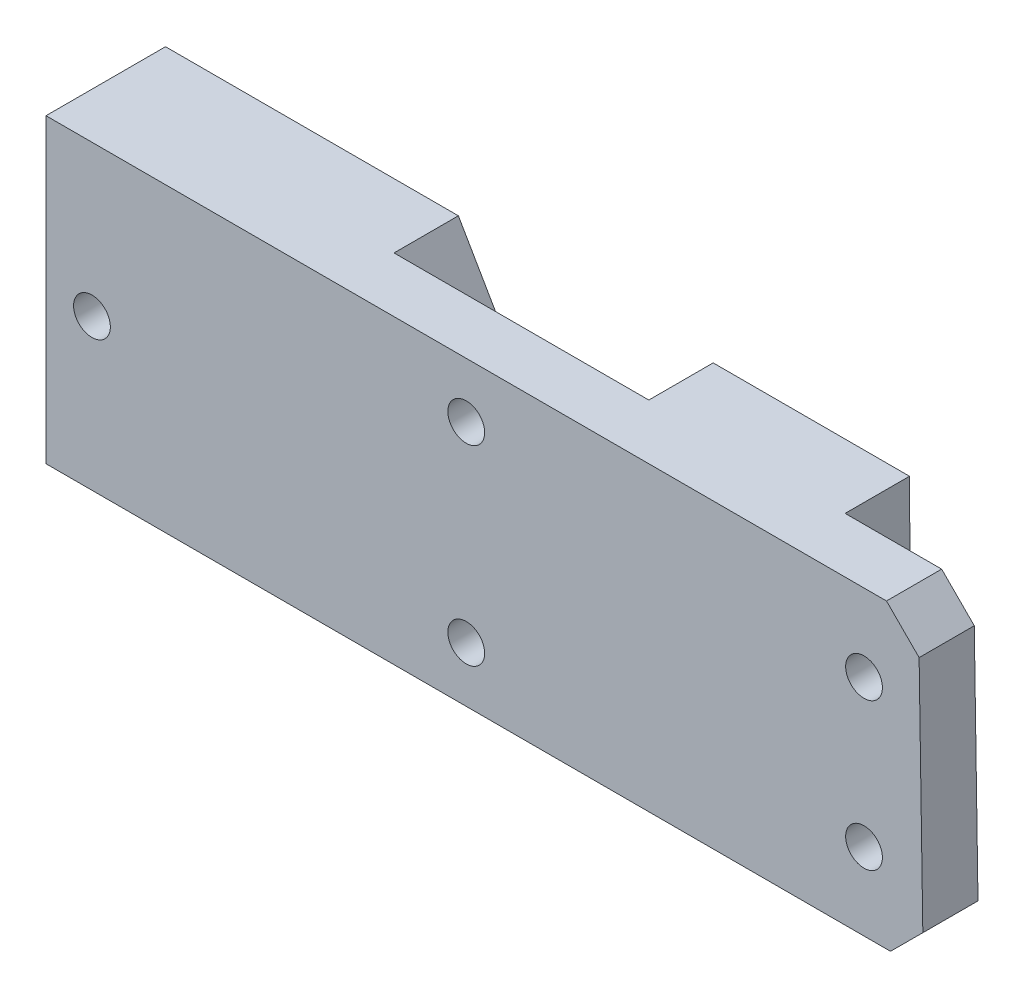
SolidWorks part; units mm, degrees
ref_plane "Front Plane" through (0, 0, 0) normal (0, 0, 1) x (1, 0, 0)
ref_plane "Top Plane" through (0, 0, 0) normal (0, 1, 0) x (1, 0, 0)
ref_plane "Right Plane" through (0, 0, 0) normal (1, 0, 0) x (0, 0, -1)
sketch "Sketch1" plane through (0, 0, 0) normal (0, 0, 1) x (1, 0, 0)
  line L0 (44.15, 19.08) -> (135.5692, 19.08)
  line L1 (12.8834, 142.2085) -> (139.1167, 15.5198) construction
  line L2 (135.5692, 19.08) -> (139.1167, 15.5198)
  line L3 (139.1167, 15.5198) -> (139.5211, -10.196)
  line L4 (139.5211, -10.196) -> (135.9992, -13.7052)
  line L5 (139.5211, -10.196) -> (12.8324, -136.4293) construction
  line L6 (135.9992, -13.7052) -> (44.15, -13.7052)
  line L7 (44.15, 19.08) -> (44.15, -13.7052)
extrude "Boss-Extrude1" add sketch "Sketch1" along normal up to surface (6 mm away)
sketch "Sketch2" plane through (0, 0, 0) normal (0, 0, -1) x (-1, 0, 0)
  line L0 (-125.0695, 19.08) -> (-125.2841, -13.7052)
  line L1 (-125.3536, -24.3126) -> (-125, 29.6874) construction
  line L2 (-135.5692, 19.08) -> (-44.15, 19.08) construction
  line L3 (-44.15, -13.7052) -> (-135.9992, -13.7052) construction
  line L4 (-125.2841, -13.7052) -> (-44.15, -13.7052)
  line L5 (-44.15, -13.7052) -> (-54.15, -3.7052)
  line L6 (-54.15, -3.7052) -> (-54.15, 9.08)
  line L7 (-54.15, 9.08) -> (-44.15, 19.08)
  line L8 (-44.15, 19.08) -> (-125.0695, 19.08)
extrude "Boss-Extrude2" add sketch "Sketch2" along normal up to surface (7 mm away)
sketch "Sketch3" plane through (0, 0, -7) normal (0, 0, -1) x (-1, 0, 0)
  circle A0 centre (-133.1246, 10.6874) radius 2
  circle A1 centre (-133.1246, -5.3126) radius 2
  circle A2 centre (-49.15, 2.6874) radius 2
  dimension "D1" = 4
  dimension "D2" = 4
  dimension "D3" = 4
extrude "Cut-Extrude1" cut sketch "Sketch3" against normal up to next
sketch "Sketch4" plane through (0, 0, 6) normal (0, 0, 1) x (1, 0, 0)
  line L0 (135.9992, -13.7052) -> (44.15, -13.7052) construction
  line L1 (76.2182, -13.7052) -> (83.1464, -25.7052)
  line L2 (83.1464, -25.7052) -> (97.0028, -25.7052)
  line L3 (97.0028, -25.7052) -> (103.931, -13.7052)
  line L4 (103.931, -13.7052) -> (97.0028, -1.7052)
  line L5 (97.0028, -1.7052) -> (83.1464, -1.7052)
  line L6 (83.1464, -1.7052) -> (76.2182, -13.7052)
  line L7 (44.15, 19.08) -> (135.5692, 19.08) construction
  line L8 (76.0032, 19.08) -> (82.9314, 7.08)
  line L9 (82.9314, 7.08) -> (96.7878, 7.08)
  line L10 (96.7878, 7.08) -> (103.716, 19.08)
  line L11 (103.716, 19.08) -> (96.7878, 31.08)
  line L12 (96.7878, 31.08) -> (82.9314, 31.08)
  line L13 (82.9314, 31.08) -> (76.0032, 19.08)
  circle A0 centre (90.0746, -13.7052) radius 12 construction
  circle A1 centre (89.8596, 19.08) radius 12 construction
  dimension "D1" = 24
  dimension "D2" = 24
extrude "Cut-Extrude2" cut sketch "Sketch4" against normal up to surface (7 mm away) from surface
sketch "Sketch5" plane through (0, 0, 0) normal (0, 0, -1) x (-1, 0, 0)
  line L0 (-76.0032, 19.08) -> (-103.716, 19.08) construction
  line L1 (-82.9314, 7.08) -> (-96.7878, 7.08) construction
  line L2 (-97.0028, -1.7052) -> (-83.1464, -1.7052) construction
  circle A0 centre (-89.8596, 13.08) radius 2
  circle A1 centre (-89.8596, -7.7052) radius 2
  point P5 (-89.8596, 19.08)
  dimension "D3" = 4
  dimension "D4" = 4
  dimension "D1" = 6
  dimension "D2" = 6
extrude "Cut-Extrude3" cut sketch "Sketch5" against normal up to next
